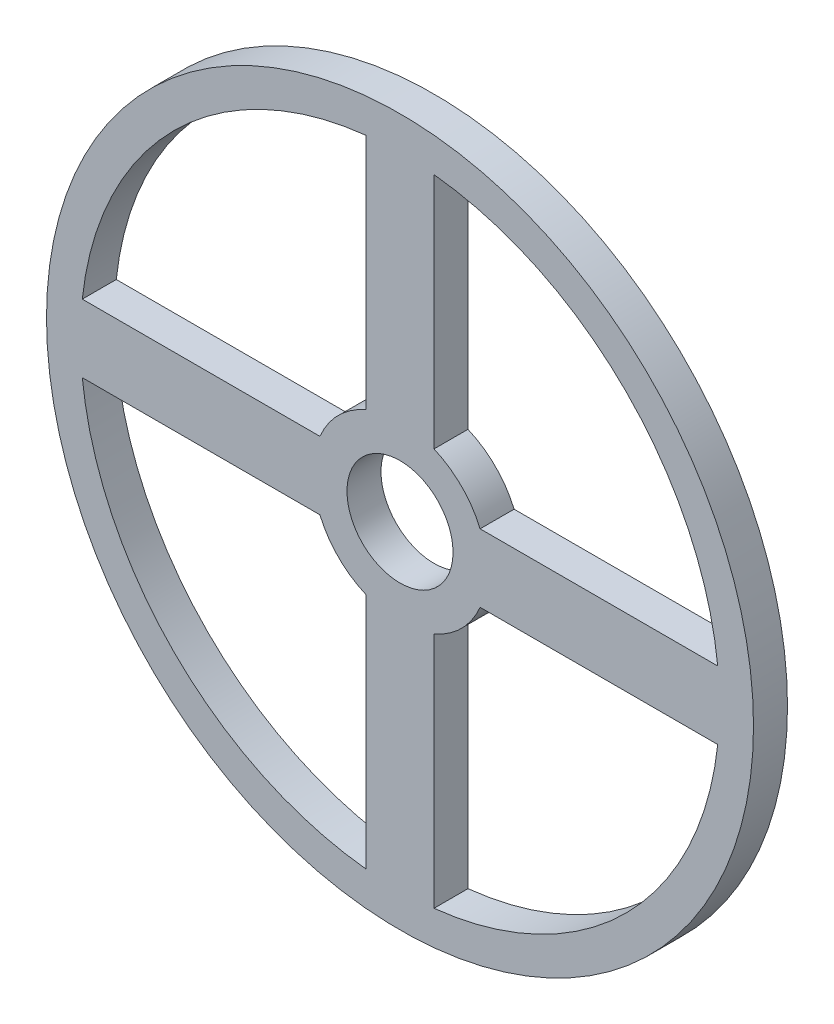
SolidWorks part; units mm, degrees
ref_plane "Front Plane" through (0, 0, 0) normal (0, 0, 1) x (1, 0, 0)
ref_plane "Top Plane" through (0, 0, 0) normal (0, 1, 0) x (1, 0, 0)
ref_plane "Right Plane" through (0, 0, 0) normal (1, 0, 0) x (0, 0, -1)
sketch "Sketch1" plane through (0, 0, 0) normal (0, 0, 1) x (1, 0, 0)
  line L0 (-7.4822, 3.175) -> (-29.6756, 3.175)
  line L1 (-3.175, 7.4822) -> (-3.175, 29.6756)
  line L2 (-4.953, 0) -> (-33.02, 0) construction
  line L3 (0, 4.953) -> (0, 33.02) construction
  line L4 (3.175, 7.4822) -> (3.175, 29.6756)
  line L5 (7.4822, 3.175) -> (29.6756, 3.175)
  line L6 (7.4822, -3.175) -> (29.6756, -3.175)
  line L7 (3.175, -7.4822) -> (3.175, -29.6756)
  line L8 (-3.175, -7.4822) -> (-3.175, -29.6756)
  line L9 (-7.4822, -3.175) -> (-29.6756, -3.175)
  circle A0 centre (0, 0) radius 33.02
  arc A2 (-33.02, 0) -> (0, 33.02) centre (0, 0) cw construction
  arc A3 (-4.953, 0) -> (0, 4.953) centre (0, 0) cw construction
  arc A4 (-29.6756, 3.175) -> (-3.175, 29.6756) centre (0, 0) cw
  arc A5 (-7.4822, 3.175) -> (-3.175, 7.4822) centre (0, 0) cw
  circle A6 centre (0, 0) radius 4.953
  arc A7 (3.175, 29.6756) -> (29.6756, 3.175) centre (0, 0) cw
  arc A8 (3.175, 7.4822) -> (7.4822, 3.175) centre (0, 0) cw
  arc A9 (29.6756, -3.175) -> (3.175, -29.6756) centre (0, 0) cw
  arc A10 (7.4822, -3.175) -> (3.175, -7.4822) centre (0, 0) cw
  arc A11 (-3.175, -29.6756) -> (-29.6756, -3.175) centre (0, 0) cw
  arc A12 (-3.175, -7.4822) -> (-7.4822, -3.175) centre (0, 0) cw
  point P31 (0, 0)
  dimension "D1" = 66.04
  dimension "D2" = 3.175
  dimension "D4" = 9.906
  dimension "D3" = 4
extrude "Boss-Extrude1" add sketch "Sketch1" along normal blind 3.175
